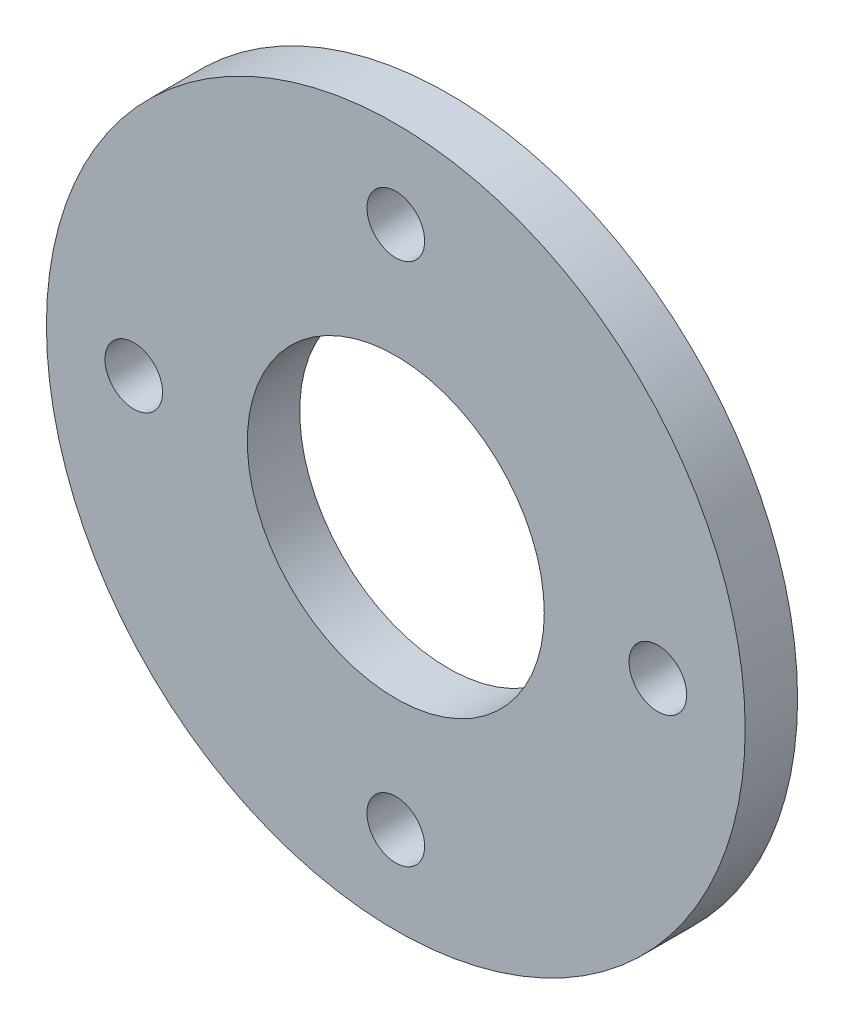
SolidWorks part; units mm, degrees
ref_plane "前视基准面" through (0, 0, 0) normal (0, 0, 1) x (1, 0, 0)
ref_plane "上视基准面" through (0, 0, 0) normal (0, 1, 0) x (1, 0, 0)
ref_plane "右视基准面" through (0, 0, 0) normal (1, 0, 0) x (0, 0, -1)
sketch "草图2" plane through (0, 0, 0) normal (0, 0, 1) x (1, 0, 0)
  circle A0 centre (0, 0) radius 8.5
  circle A1 centre (0, 0) radius 15
  circle A2 centre (0, 0) radius 20
  circle A3 centre (0, 15) radius 1.65
  circle A4 centre (15, 0) radius 1.65
  circle A5 centre (-15, 0) radius 1.65
  circle A6 centre (0, -15) radius 1.65
extrude "凸台-拉伸1" add sketch "草图2" along normal blind 3 contours A2 A6 A1 A5 A3 A4 | A6 A1 A4 A3 A5 A0
